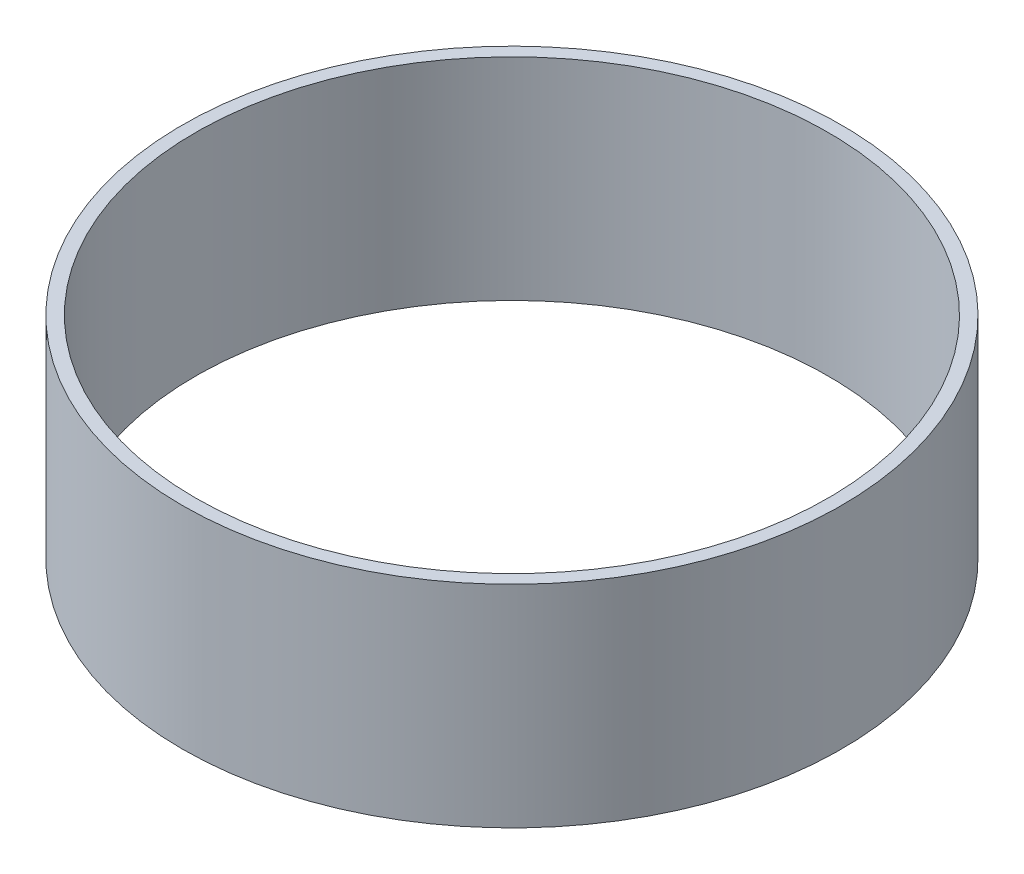
SolidWorks part; units mm, degrees
ref_plane "Front Plane" through (0, 0, 0) normal (0, 0, 1) x (1, 0, 0)
ref_plane "Top Plane" through (0, 0, 0) normal (0, 1, 0) x (1, 0, 0)
ref_plane "Right Plane" through (0, 0, 0) normal (1, 0, 0) x (0, 0, -1)
sketch "Sketch1" plane through (0, 0, 0) normal (0, 1, 0) x (1, 0, 0)
  circle A0 centre (0, 0) radius 38.1
  circle A1 centre (0, 0) radius 39.6748
  dimension "D1" = 76.2
  dimension "D2" = 79.3496
extrude "Boss-Extrude1" add sketch "Sketch1" along normal mid plane 25.4
equation "\"airframeInnerDiameter\"=3"
equation "\"ATSBayInnerDiameter\"=2.88"
equation "\"ATSBayLength\"=5.5"
equation "\"ATSBandLength\"=1"
equation "\"ATSCouplerOuter\"=\"airframeInnerDiameter\""
equation "\"ATSOffsetFromAft\"=1.5"
equation "\"D1@Sketch1\"=\"ATSCouplerOuter\""
equation "\"outerDiameter\"=3.124"
equation "\"D2@Sketch1\"=\"outerDiameter\""
equation "\"D1@Boss-Extrude1\"=\"ATSBandLength\""
